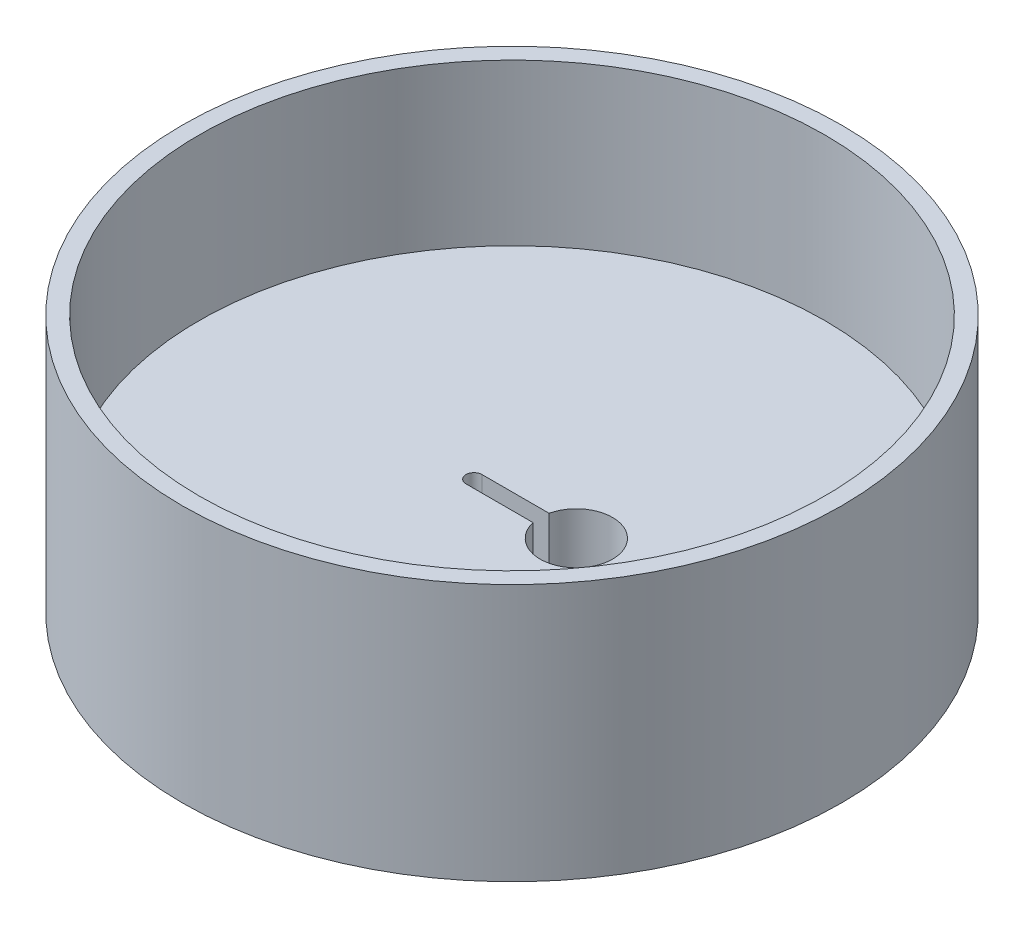
SolidWorks part; units mm, degrees
ref_plane "Front Plane" through (0, 0, 0) normal (0, 0, 1) x (1, 0, 0)
ref_plane "Top Plane" through (0, 0, 0) normal (0, 1, 0) x (1, 0, 0)
ref_plane "Right Plane" through (0, 0, 0) normal (1, 0, 0) x (0, 0, -1)
sketch "Sketch1" plane through (0, 0, 0) normal (0, 1, 0) x (1, 0, 0)
  line L0 (1.75, 0) -> (-2.3632, 0) construction
  line L1 (1.8063, -0.5) -> (-2.3632, -0.5)
  line L2 (1.8063, 0.5) -> (-2.3632, 0.5)
  circle A0 centre (0, 0) radius 19.45
  arc A2 (1.8063, -0.5) -> (1.8063, 0.5) centre (4, 0) ccw
  arc A4 (-2.3632, 0.5) -> (-2.3632, -0.5) centre (-2.3632, 0) ccw
  point P6 (-0.3066, 0)
  dimension "D1" = 4.5
  dimension "D2" = 38.9
  dimension "D5" = 0.5
  dimension "D3" = 4
  dimension "D4" = 0.5
  dimension "D6" = 0.5
extrude "Boss-Extrude1" add sketch "Sketch1" along normal blind 6
sketch "Sketch2" plane through (0, 6, 0) normal (0, 1, 0) x (1, 0, 0)
  circle A0 centre (0, 0) radius 20.5
  circle A1 centre (0, 0) radius 19.45
  circle A2 centre (0, 0) radius 19.45 construction
  point P6 (0, -20.5)
  point P7 (0, -19.45)
  dimension "D1" = 41
extrude "Boss-Extrude2" add sketch "Sketch2" along normal blind 10 and the other way up to surface (6 mm away) other way up to face at (0, 0, 19.45)
